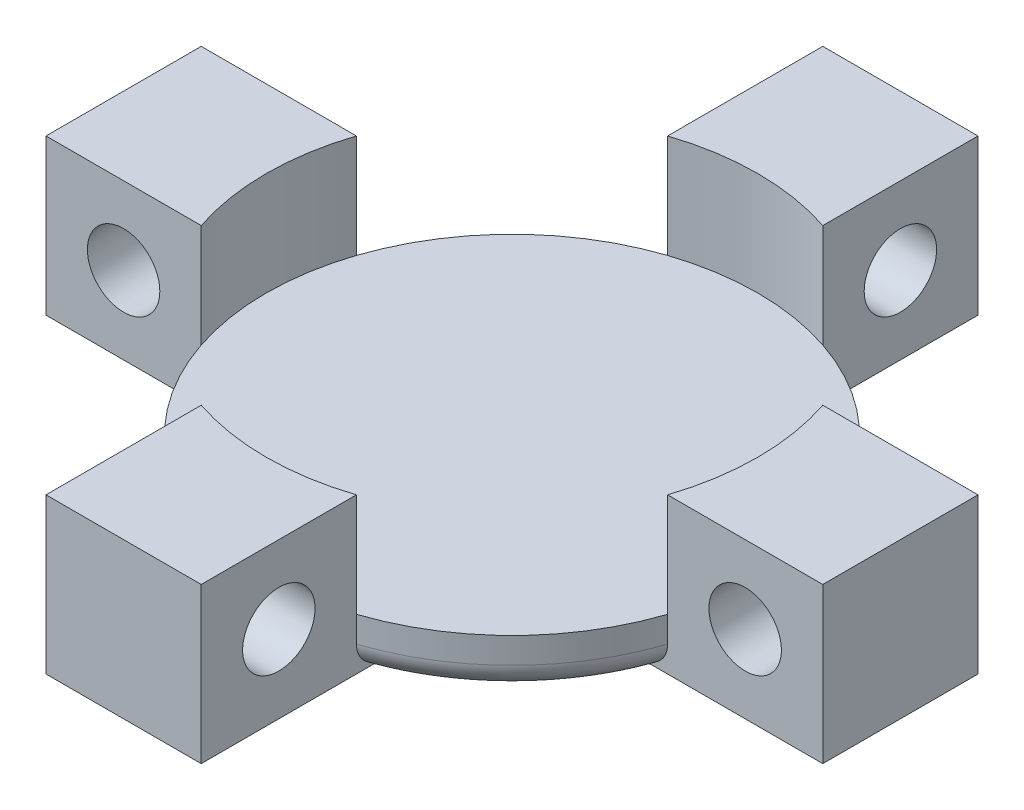
SolidWorks part; units mm, degrees
ref_plane "Front Plane" through (0, 0, 0) normal (0, 0, 1) x (1, 0, 0)
ref_plane "Top Plane" through (0, 0, 0) normal (0, 1, 0) x (1, 0, 0)
ref_plane "Right Plane" through (0, 0, 0) normal (1, 0, 0) x (0, 0, -1)
sketch "Sketch2" plane through (0, 0, 0) normal (0, 1, 0) x (1, 0, 0)
  circle A0 centre (0, 0) radius 12.065
  dimension "D1" = 24.13
extrude "Boss-Extrude1" add sketch "Sketch2" along normal blind 2.54
sketch "Sketch3" plane through (0, 0, 0) normal (0, 1, 0) x (1, 0, 0)
  line L0 (-11.4476, 3.81) -> (-19.0676, 3.81)
  line L1 (-19.0676, 3.81) -> (-19.0676, -3.81)
  line L2 (-19.0676, -3.81) -> (-11.4476, -3.81)
  arc A0 (-11.4476, 3.81) -> (-11.4476, -3.81) centre (0, 0) ccw
  circle A1 centre (0, 0) radius 12.065 construction
  dimension "D1" = 7.62
  dimension "D2" = 7.62
  dimension "D3" = 7.62
extrude "Boss-Extrude2" add sketch "Sketch3" along normal blind 7.62
pattern_circular "CirPattern1" count 4 over 360 about axis through (0, 0, 0) along (0, 1, 0) of "Boss-Extrude2"
sketch "Sketch4" plane through (0, 0, 3.81) normal (0, 0, 1) x (1, 0, 0)
  line L0 (-19.0676, 7.62) -> (-11.4476, 7.62) construction
  line L1 (-19.0676, 7.62) -> (-19.0676, 0) construction
  circle A0 centre (-15.2576, 3.81) radius 1.778
  point P4 (-15.2576, 7.62)
  point P7 (-19.0676, 3.81)
  dimension "D1" = 3.556
extrude "Cut-Extrude1" cut sketch "Sketch4" against normal blind 7.62
pattern_circular "CirPattern2" count 4 over 360 about axis through (0, 2.54, 0) along (0, -1, 0) of "Cut-Extrude1"
fillet "Fillet1" radius 1.27 4 edges at (-8.5312, 0, -8.5312) (8.5312, 0, -8.5312) (8.5312, 0, 8.5312) (-8.5312, 0, 8.5312)
